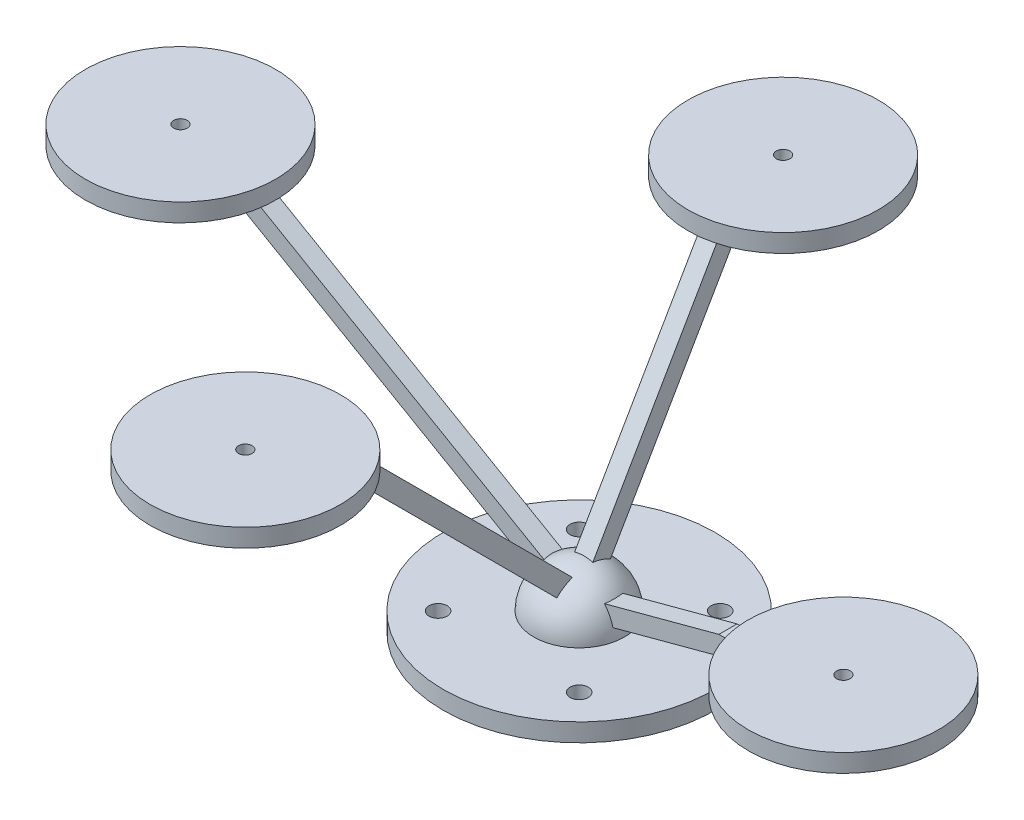
SolidWorks part; units mm, degrees
ref_plane "前视基准面" through (0, 0, 0) normal (0, 0, 1) x (1, 0, 0)
ref_plane "上视基准面" through (0, 0, 0) normal (0, 1, 0) x (1, 0, 0)
ref_plane "右视基准面" through (0, 0, 0) normal (1, 0, 0) x (0, 0, -1)
sketch "草图1" plane through (0, 0, 0) normal (0, 1, 0) x (1, 0, 0)
  line L0 (-23.4221, 0) -> (25.8766, 0) construction
  line L1 (0, 26.1921) -> (0, -25.0701) construction
  line L2 (-18.9498, 18.9498) -> (18.8862, -18.8862) construction
  line L3 (18.9424, 18.9424) -> (-20.2044, -20.2044) construction
  circle A0 centre (0, 0) radius 15
  circle A1 centre (0, 0) radius 11 construction
  circle A2 centre (7.7782, 7.7782) radius 1
  circle A3 centre (-7.7782, 7.7782) radius 1
  circle A4 centre (-7.7782, -7.7782) radius 1
  circle A5 centre (7.7782, -7.7782) radius 1
  dimension "D1" = 30
  dimension "D4" = 22
  dimension "D5" = 2
  dimension "D2" = 45
  dimension "D3" = 45
extrude "凸台-拉伸1" add sketch "草图1" along normal blind 2
sketch "草图2" plane through (0, 0, 0) normal (1, 0, 0) x (0, 0, -1)
  line L0 (0, 2) -> (0, 7)
  line L1 (15, 2) -> (-15, 2) construction
  line L2 (0, 2) -> (5, 2)
  arc A0 (0, 7) -> (5, 2) centre (0, 2) cw
  dimension "D1" = 5
revolve "旋转1" add sketch "草图2" angle 360 about L0
sketch "草图3" plane through (0, 0, 0) normal (0, 0, 1) x (1, 0, 0)
  line L0 (0, 2) -> (0, 9.7216) construction
  line L1 (15, 2) -> (-15, 2) construction
  line L2 (0, 2) -> (24.1481, 8.4705)
  line L3 (8.7782, 2) -> (6.7782, 2) construction
  line L4 (0, 4.0706) -> (16.4207, 8.4705)
  line L6 (16.4207, 8.4705) -> (24.1481, 8.4705)
  line L7 (0, 2) -> (-38.9711, 24.5)
  line L8 (-34.9711, 24.5) -> (0, 4.3094)
  line L9 (0, 4.3094) -> (0, 4.0706)
  line L10 (-38.9711, 24.5) -> (-34.9711, 24.5)
  dimension "D1" = 15
  dimension "D2" = 25
  dimension "D3" = 2
  dimension "D4" = 30
  dimension "D5" = 45
  dimension "D6" = 2
extrude "凸台-拉伸2" add sketch "草图3" along normal mid plane 2
sketch "草图4" plane through (0, 8.4705, 0) normal (0, 1, 0) x (1, 0, 0)
  line L0 (24.1481, -1) -> (24.1481, 1) construction
  circle A0 centre (29.1481, 0) radius 10.5
  circle A1 centre (29.1481, 0) radius 0.75
  dimension "D1" = 21
  dimension "D2" = 1.5
  dimension "D3" = 5
extrude "凸台-拉伸3" add sketch "草图4" along normal blind 2
sketch "草图5" plane through (0, 24.5, 0) normal (0, 1, 0) x (1, 0, 0)
  line L0 (-38.9711, -1) -> (-38.9711, 1) construction
  circle A0 centre (-43.9711, 0) radius 10.5
  circle A1 centre (-43.9711, 0) radius 0.75
  dimension "D1" = 21
  dimension "D2" = 1.5
  dimension "D3" = 5
extrude "凸台-拉伸4" add sketch "草图5" along normal blind 2
sketch "草图6" plane through (0, 0, 0) normal (1, 0, 0) x (0, 0, -1)
  line L0 (0, 0) -> (0, 10.6928) construction
  line L1 (0, 2) -> (17.5, 32.3109)
  line L2 (15, 2) -> (-15, 2) construction
  line L3 (8.7782, 2) -> (6.7782, 2) construction
  line L4 (0, 6) -> (15.1906, 32.3109)
  line L5 (15.1906, 32.3109) -> (17.5, 32.3109)
  line L6 (0, 2) -> (-31.8198, 33.8198)
  line L7 (0, 4.8284) -> (-28.9914, 33.8198)
  line L8 (-31.8198, 33.8198) -> (-28.9914, 33.8198)
  line L10 (0, 6) -> (0, 4.8284)
  dimension "D1" = 60
  dimension "D2" = 35
  dimension "D3" = 2
  dimension "D4" = 45
  dimension "D5" = 45
  dimension "D6" = 2
extrude "凸台-拉伸5" add sketch "草图6" along normal mid plane 2
sketch "草图7" plane through (0, 32.3109, 0) normal (0, 1, 0) x (1, 0, 0)
  line L0 (1, 17.5) -> (-1, 17.5) construction
  circle A0 centre (0, 22.5) radius 10.5
  circle A1 centre (0, 22.5) radius 0.75
  dimension "D1" = 21
  dimension "D2" = 1.5
  dimension "D3" = 5
extrude "凸台-拉伸6" add sketch "草图7" along normal blind 2
sketch "草图8" plane through (0, 33.8198, 0) normal (0, 1, 0) x (1, 0, 0)
  line L0 (1, -31.8198) -> (-1, -31.8198) construction
  circle A0 centre (0, -36.8198) radius 10.5
  circle A1 centre (0, -36.8198) radius 0.75
  dimension "D1" = 1.5
  dimension "D2" = 21
  dimension "D3" = 5
extrude "凸台-拉伸7" add sketch "草图8" along normal blind 2
